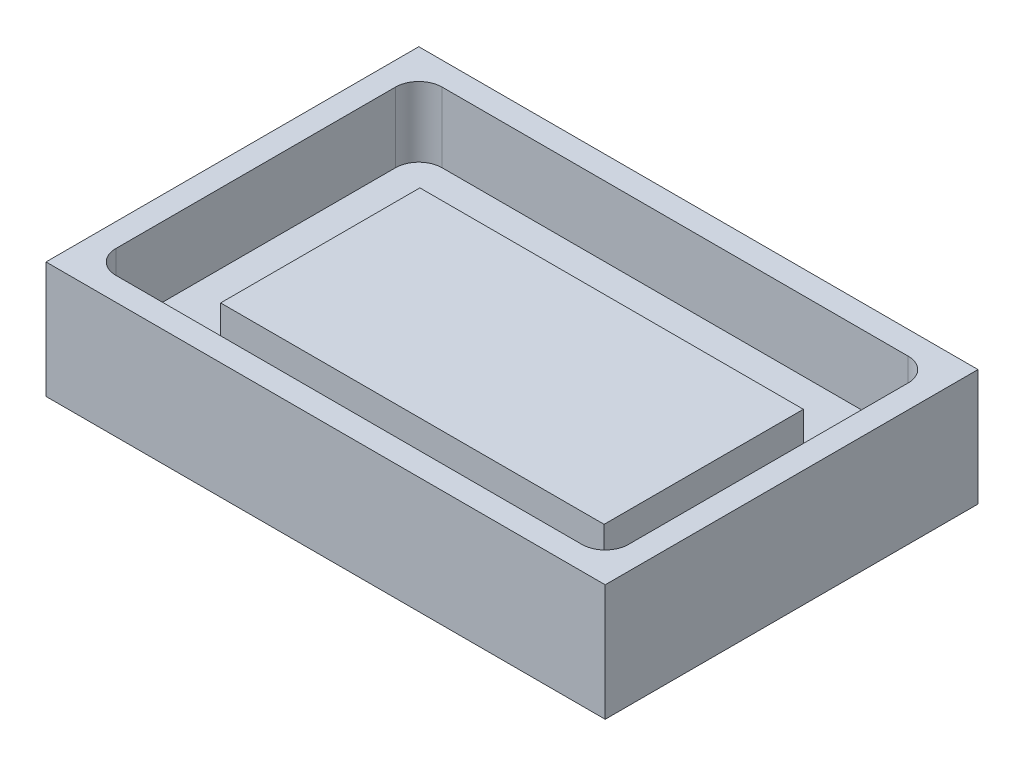
SolidWorks part; units mm, degrees
ref_plane "Front Plane" through (0, 0, 0) normal (0, 0, 1) x (1, 0, 0)
ref_plane "Top Plane" through (0, 0, 0) normal (0, 1, 0) x (1, 0, 0)
ref_plane "Right Plane" through (0, 0, 0) normal (1, 0, 0) x (0, 0, -1)
sketch "Sketch4" plane through (0, 0, 0) normal (0, 1, 0) x (1, 0, 0)
  line L1 (0, 0) -> (76.2, 0)
  line L2 (0, 0) -> (0, 50.8)
  line L3 (0, 50.8) -> (76.2, 50.8)
  line L4 (76.2, 0) -> (76.2, 50.8)
extrude "Extrude2" add sketch "Sketch4" against normal blind 15.875
sketch "Sketch5" plane through (0, 0, 0) normal (0, 1, 0) x (1, 0, 0)
  line L8 (3.175, 44.45) -> (3.175, 6.35)
  line L9 (6.35, 3.175) -> (69.85, 3.175)
  line L10 (73.025, 6.35) -> (73.025, 44.45)
  line L11 (69.85, 47.625) -> (6.35, 47.625)
  arc A0 (3.175, 44.45) -> (6.35, 47.625) centre (6.35, 44.45) cw
  arc A1 (3.175, 6.35) -> (6.35, 3.175) centre (6.35, 6.35) ccw
  arc A2 (69.85, 3.175) -> (73.025, 6.35) centre (69.85, 6.35) ccw
  arc A3 (73.025, 44.45) -> (69.85, 47.625) centre (69.85, 44.45) ccw
extrude "Extrude3" cut sketch "Sketch5" against normal blind 9.525
ref_plane "Plane1" through (0, -9.525, 0) normal (0, 1, 0) x (-1, 0, 0)
sketch "Sketch6" plane through (0, -9.525, 0) normal (0, 1, 0) x (-1, 0, 0)
  line L4 (-11.9718, -11.8232) -> (-64.2282, -11.8232)
  line L5 (-11.9718, -11.8232) -> (-11.9718, -38.9768)
  line L6 (-11.9718, -38.9768) -> (-64.2282, -38.9768)
  line L7 (-64.2282, -11.8232) -> (-64.2282, -38.9768)
  point P6 (-38.1, -25.4)
extrude "Extrude4" add sketch "Sketch6" along normal blind 4.7625
sketch "Sketch7" plane through (0, 0, 0) normal (0, 1, 0) x (1, 0, 0)
  line L0 (11.9718, 25.4) -> (64.2282, 25.4) construction
  line L1 (11.9718, 38.9768) -> (11.9718, 11.8232) construction
  line L2 (64.2282, 11.8232) -> (64.2282, 38.9768) construction
  line L3 (24.1101, 25.4) -> (52.0899, 25.4) construction
  line L4 (24.1101, 32.3949) -> (52.0899, 32.3949)
  line L5 (24.1101, 18.4051) -> (52.0899, 18.4051)
  arc A0 (24.1101, 32.3949) -> (24.1101, 18.4051) centre (24.1101, 25.4) ccw
  arc A1 (52.0899, 18.4051) -> (52.0899, 32.3949) centre (52.0899, 25.4) ccw
  point P8 (38.1, 25.4)
